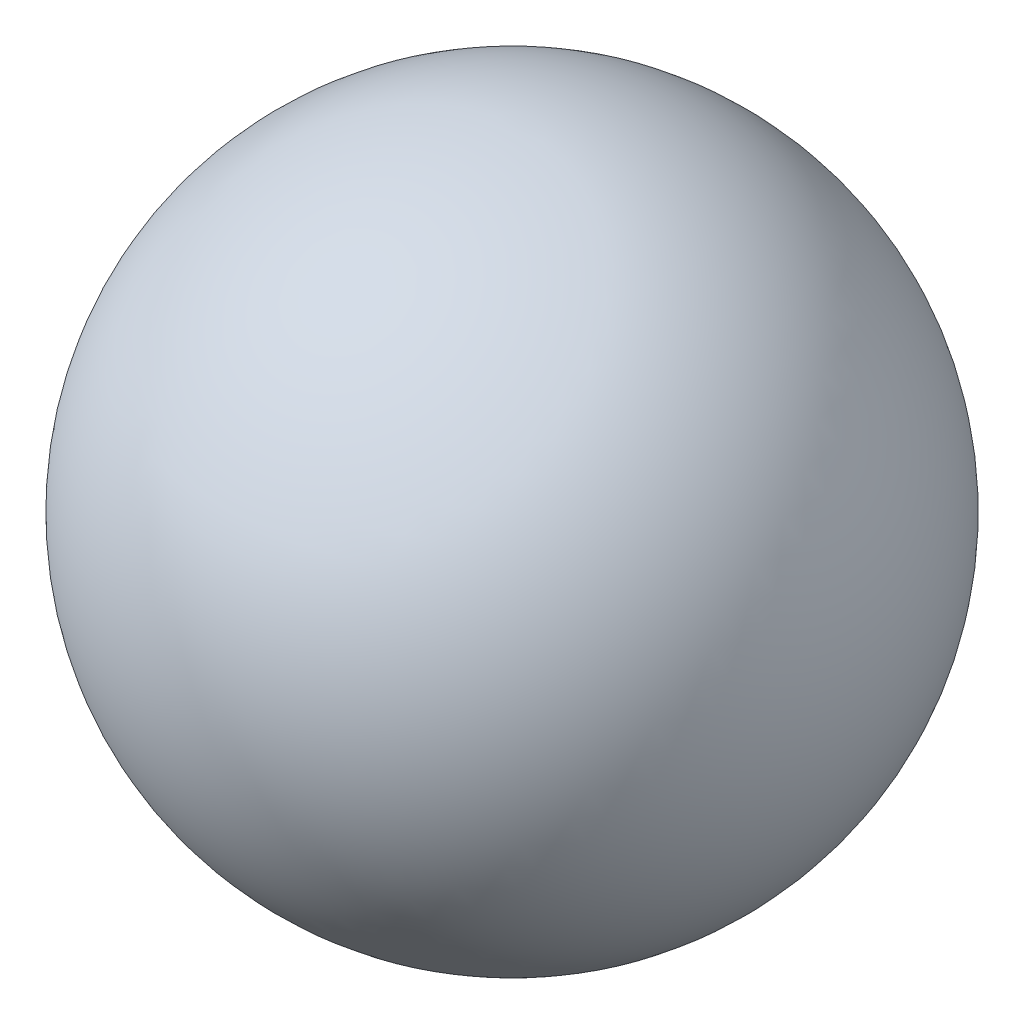
SolidWorks part; units mm, degrees
ref_plane "Front Plane" through (0, 0, 0) normal (0, 0, 1) x (1, 0, 0)
ref_plane "Top Plane" through (0, 0, 0) normal (0, 1, 0) x (1, 0, 0)
ref_plane "Right Plane" through (0, 0, 0) normal (1, 0, 0) x (0, 0, -1)
sketch "Sketch1" plane through (0, 0, 0) normal (0, 0, 1) x (1, 0, 0)
  line L0 (0, 56.5928) -> (0, -67.204) construction
  arc A0 (0, 304.8) -> (0, -304.8) centre (0, 0) cw
  dimension "D1" = 304.8
revolve "Revolve-Thin1" add sketch "Sketch1" angle 360 about L0
